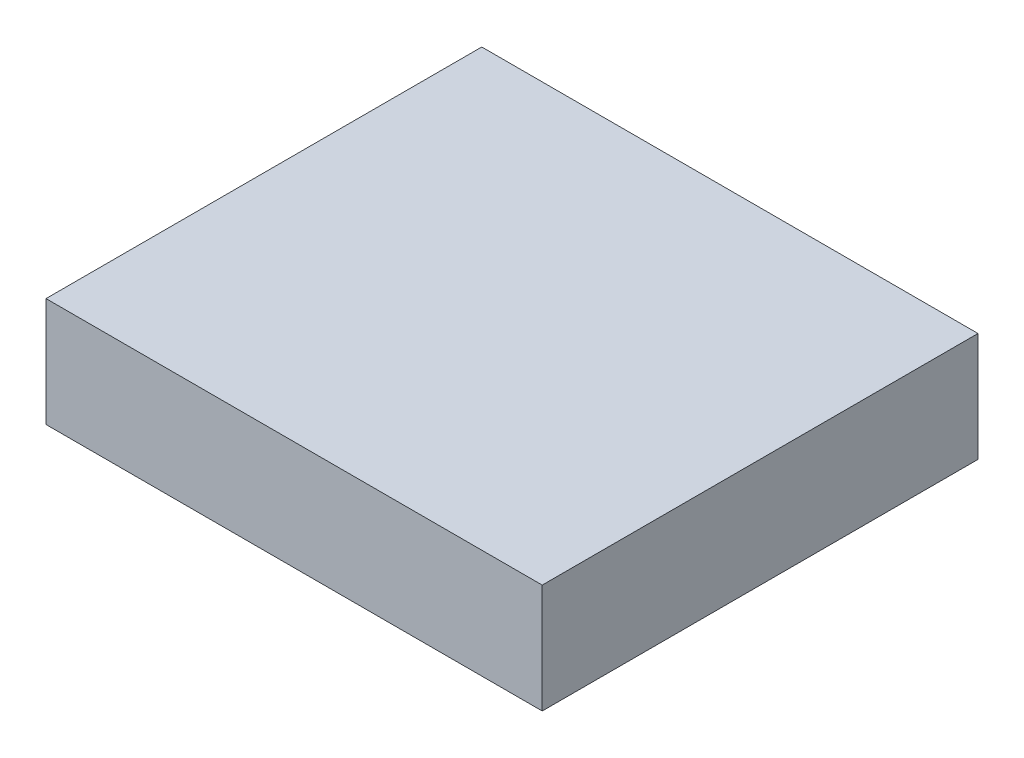
SolidWorks part; units mm, degrees
ref_plane "Front Plane" through (0, 0, 0) normal (0, 0, 1) x (1, 0, 0)
ref_plane "Top Plane" through (0, 0, 0) normal (0, 1, 0) x (1, 0, 0)
ref_plane "Right Plane" through (0, 0, 0) normal (1, 0, 0) x (0, 0, -1)
sketch "Sketch1" plane through (0, 0, 0) normal (0, 1, 0) x (1, 0, 0)
  line L1 (0, 0) -> (5.0038, 0)
  line L2 (0, 0) -> (0, 4.3942)
  line L3 (0, 4.3942) -> (5.0038, 4.3942)
  line L4 (5.0038, 0) -> (5.0038, 4.3942)
  dimension "D1" = 4.3942
  dimension "D2" = 5.0038
extrude "Boss-Extrude1" add sketch "Sketch1" along normal blind 1.0998
